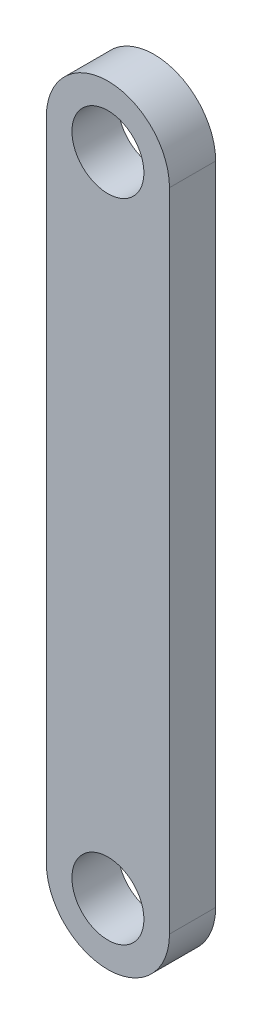
SolidWorks part; units mm, degrees
ref_plane "Front Plane" through (0, 0, 0) normal (0, 0, 1) x (1, 0, 0)
ref_plane "Top Plane" through (0, 0, 0) normal (0, 1, 0) x (1, 0, 0)
ref_plane "Right Plane" through (0, 0, 0) normal (1, 0, 0) x (0, 0, -1)
sketch "Sketch1" plane through (0, 0, 0) normal (0, 0, 1) x (1, 0, 0)
  line L3 (-4, 42) -> (-4, 0)
  line L4 (1.65, 0) -> (-1.65, 0) construction
  line L5 (4, 42) -> (4, 0)
  circle A2 centre (0, 0) radius 2.34
  circle A3 centre (0, 42) radius 2.34
  arc A4 (4, 42) -> (-4, 42) centre (0, 42) ccw
  arc A5 (-4, 0) -> (4, 0) centre (0, 0) ccw
  dimension "D1" = 8
  dimension "D2" = 4.68
  dimension "D3" = 42
extrude "Boss-Extrude1" add sketch "Sketch1" along normal blind 3
equation "\"bScale\"= 10"
equation "\"lScale\"= 10"
equation "\"D1@Sketch1\"=.8*\"bScale\""
equation "\"D2@Sketch1\"=0.468 * \"bScale\""
equation "\"D3@Sketch1\"=4.2*\"lScale\""
